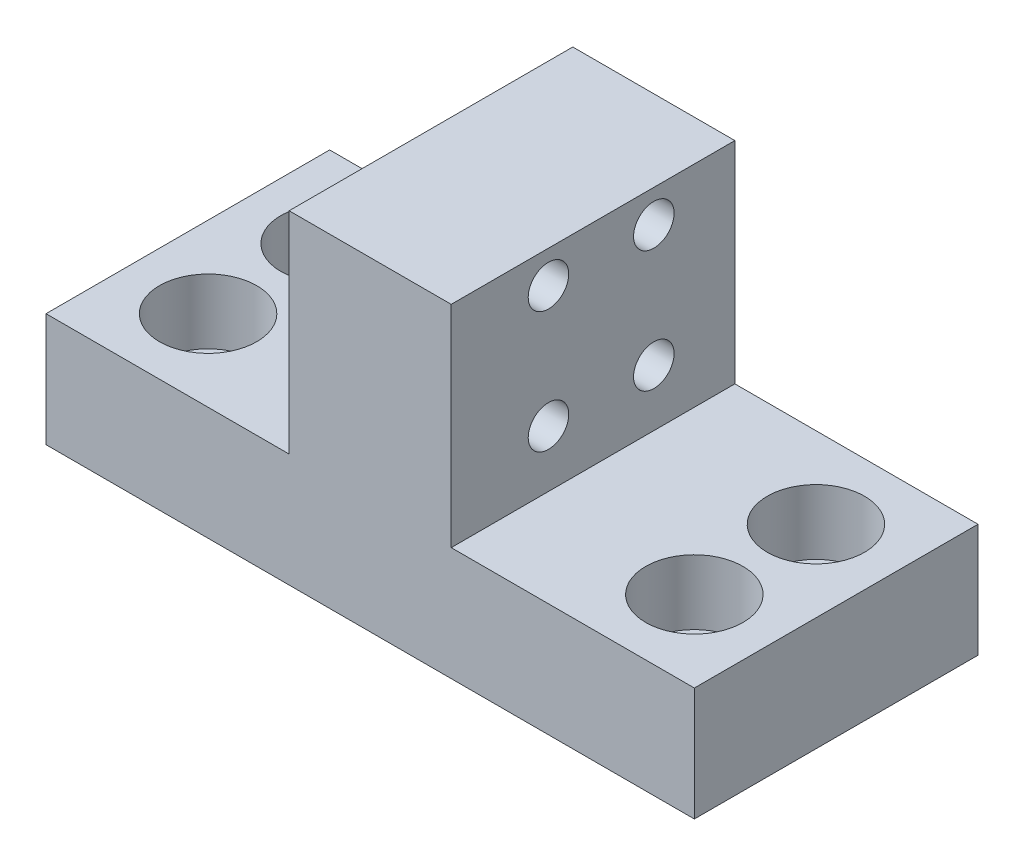
SolidWorks part; units mm, degrees
ref_plane "前视基准面" through (0, 0, 0) normal (0, 0, 1) x (1, 0, 0)
ref_plane "上视基准面" through (0, 0, 0) normal (0, 1, 0) x (1, 0, 0)
ref_plane "右视基准面" through (0, 0, 0) normal (1, 0, 0) x (0, 0, -1)
sketch "草图1" plane through (0, 0, 0) normal (0, 1, 0) x (1, 0, 0)
  line L0 (-40, 17.5) -> (-40, -17.5)
  line L1 (-40, -17.5) -> (40, -17.5)
  line L2 (40, -17.5) -> (40, 17.5)
  line L3 (40, 17.5) -> (-40, 17.5)
  line L4 (0, 0) -> (80, 0) construction
  line L5 (0, 0) -> (0, 15.8626) construction
  point P10 (0, 17.5)
  point P12 (40, 0)
  dimension "D1" = 35
  dimension "D2" = 80
extrude "凸台-拉伸1" add sketch "草图1" along normal blind 14
sketch "草图2" plane through (0, 14, 0) normal (0, 1, 0) x (1, 0, 0)
  line L0 (0, 0) -> (0, 23.1433) construction
  line L1 (0, 0) -> (16.8315, 0) construction
  line L2 (-10, 17.5) -> (-10, -17.5)
  line L3 (40, 17.5) -> (-40, 17.5) construction
  line L4 (-40, -17.5) -> (40, -17.5) construction
  line L5 (10, -17.5) -> (10, 17.5)
  line L6 (10, 17.5) -> (-10, 17.5)
  line L7 (10, -17.5) -> (-10, -17.5)
  point P12 (0, 17.5)
  dimension "D1" = 20
extrude "凸台-拉伸2" add sketch "草图2" along normal blind 26
hole_wizard "M20 六角头螺栓的柱形沉头孔1" positions "草图3" profile "草图4" counterbore size "M20" standard "GB" end condition up to next
sketch "草图3" plane through (0, 14, 0) normal (0, 1, 0) x (1, 0, 0)
  line L0 (-10, 17.5) -> (-40, 17.5) construction
  point P0 (-30, 7.5)
  dimension "D1" = 10
  dimension "D2" = 30
sketch "草图4" plane through (-30, 14, -7.5) normal (1, 0, 0) x (0, 0, 1)
  line L0 (0, 0) -> (0, 14.001)
  line L1 (0, 14.001) -> (3.5, 14.001)
  line L3 (3.5, 14.001) -> (3.5, 8)
  line L4 (3.5, 8) -> (6, 8)
  line L5 (6, 8) -> (6, 0)
  line L7 (6, 0) -> (0, 0)
  line L11 (0, -6.35) -> (0, 107.95) construction
  dimension "通孔孔直径" = 7
  dimension "通孔孔深度" = 14.001
  dimension "柱形沉头孔直径" = 12
  dimension "柱形沉头孔深度" = 8
pattern_linear "阵列(线性)1" count 2 spacing 60 along (1, 0, 0) count 2 spacing 15 along (0, 0, 1) of "M20 六角头螺栓的柱形沉头孔1"
sketch "草图5" plane through (-10, 0, 0) normal (-1, 0, 0) x (0, 0, 1)
  line L0 (-17.5, 0) -> (17.5, 0) construction
  circle A0 centre (-7.5, 21) radius 2.5
  dimension "D1" = 5
  dimension "D2" = 21
  dimension "D3" = 7.5
extrude "切除-拉伸1" cut sketch "草图5" against normal through all
pattern_linear "阵列(线性)2" count 2 spacing 13 along (0, 0, 1) count 2 spacing 15 along (0, 1, 0) of "切除-拉伸1"
